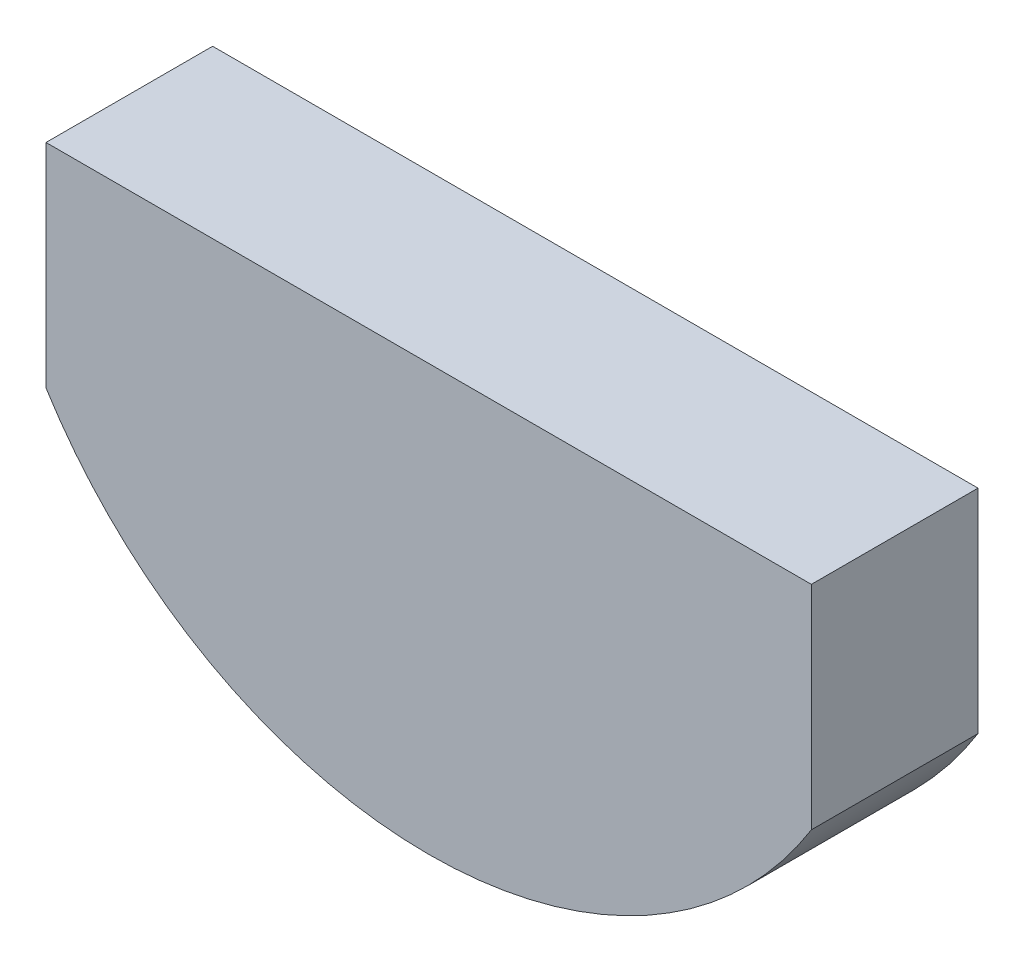
SolidWorks part; units mm, degrees
ref_plane "Front Plane" through (0, 0, 0) normal (0, 0, 1) x (1, 0, 0)
ref_plane "Top Plane" through (0, 0, 0) normal (0, 1, 0) x (1, 0, 0)
ref_plane "Right Plane" through (0, 0, 0) normal (1, 0, 0) x (0, 0, -1)
sketch "Sketch1" plane through (0, 0, 0) normal (0, 1, 0) x (1, 0, 0)
  line L1 (-90, -55) -> (90, -55)
  line L2 (-90, -55) -> (-90, 55)
  line L3 (-90, 55) -> (90, 55)
  line L4 (90, -55) -> (90, 55)
  line L5 (-90, -55) -> (90, 55) construction
  line L6 (-90, 55) -> (90, -55) construction
  point P0 (0, 0)
  dimension "D1" = 110
  dimension "D2" = 180
extrude "Boss-Extrude1" add sketch "Sketch1" along normal blind 50
sketch "Sketch2" plane through (-35, 0, -55) normal (0, 0, 1) x (1, 0, 0)
  line L2 (-55, 0) -> (125, 0) construction
  line L3 (-55, 0) -> (125, 0)
  arc A1 (-55, 0) -> (125, 0) centre (35, 56) ccw
  point P3 (35, -50)
  dimension "D1" = 50
extrude "Boss-Extrude2" add sketch "Sketch2" along normal up to surface (110 mm away) up to face at (0, 25, 55)
sketch "Sketch3" plane through (0, 50, 0) normal (0, 1, 0) x (1, 0, 0)
  line L0 (-49.1188, -55) -> (-90, 15.8083)
  line L1 (-90, -55) -> (90, -55) construction
  line L2 (-90, 55) -> (-90, -55) construction
  line L3 (-90, 15.8083) -> (-90, -55)
  line L4 (-90, -55) -> (-49.1188, -55)
  dimension "D1" = 30
extrude "Cut-Extrude1" cut sketch "Sketch3" against normal through all
mirror "Mirror1" about plane through (0, 0, 0) normal (1, 0, 0) of "Cut-Extrude1"
sketch "Sketch4" plane through (-60.6548, 0, 35.0191) normal (-0.866, 0, 0.5) x (0.5, 0, 0.866)
  line L0 (-20.9652, 42.9426) -> (-20.9652, -7.0574)
  arc A1 (-20.9652, 42.9426) -> (-20.9652, -7.0574) centre (-20.9652, 17.9426) cw
  dimension "D1" = 50
sketch "Sketch5" plane through (0, 0, -55) normal (0, 0, -1) x (-1, 0, 0)
  circle A0 centre (0, 0) radius 5
  dimension "D1" = 0
extrude "Boss-Extrude5" add sketch "Sketch5" along normal blind 10 and the other way blind 10
revolve "Revolve1" add sketch "Sketch4" angle 360 about L0
mirror "Mirror2" about plane through (0, 0, 0) normal (1, 0, 0) of "Revolve1"
sketch "Sketch6" plane through (0, 50, 0) normal (0, 1, 0) x (1, 0, 0)
  line L1 (-109.7278, 15.8083) -> (109.0603, 15.8083)
  line L2 (-109.7278, 15.8083) -> (-109.7278, -56.0711)
  line L3 (-109.7278, -56.0711) -> (109.0603, -56.0711)
  line L4 (109.0603, 15.8083) -> (109.0603, -56.0711)
extrude "Cut-Extrude2" cut sketch "Sketch6" against normal blind 126
